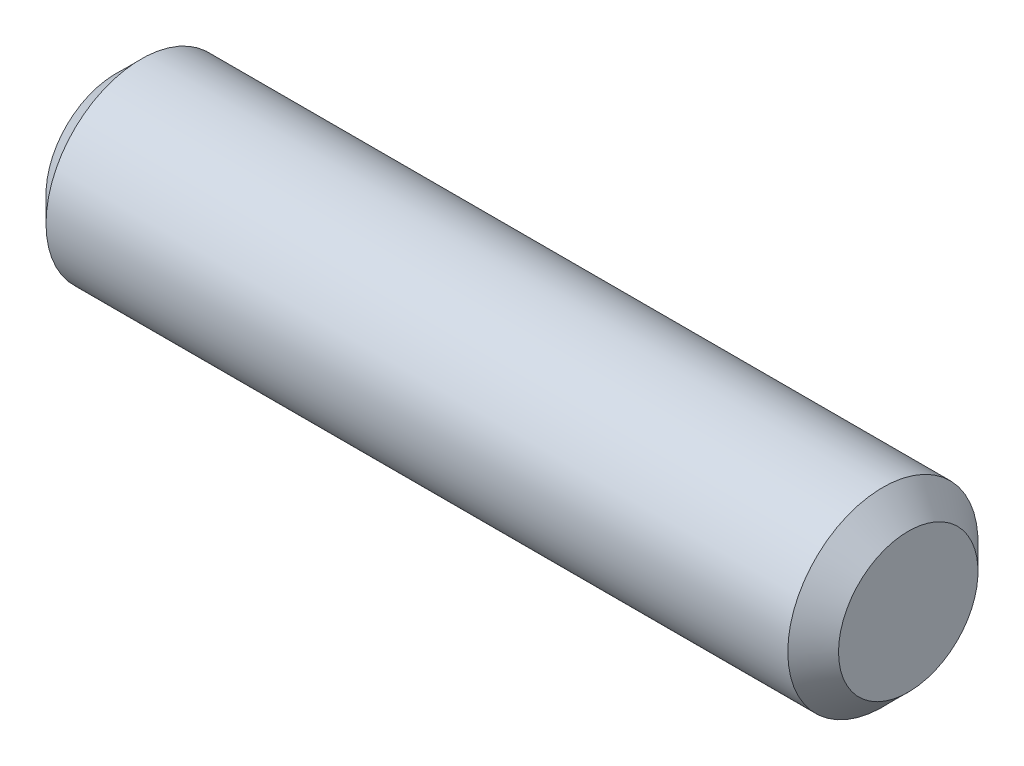
SolidWorks part; units mm, degrees
ref_plane "前视基准面" through (0, 0, 0) normal (0, 0, 1) x (1, 0, 0)
ref_plane "上视基准面" through (0, 0, 0) normal (0, 1, 0) x (1, 0, 0)
ref_plane "右视基准面" through (0, 0, 0) normal (1, 0, 0) x (0, 0, -1)
sketch "草图1" plane through (0, 0, 0) normal (0, 0, 1) x (1, 0, 0)
  line L0 (-6.3202, 0) -> (6.9944, 0) construction
  line L1 (-5.3427, 0) -> (-5.3427, 3)
  line L2 (-5.3427, 3) -> (19.6573, 3)
  line L3 (19.6573, 3) -> (19.6573, 0)
  line L4 (-5.3427, 0) -> (19.6573, 0)
  dimension "D1" = 25
  dimension "D2" = 3
revolve "旋转1" add sketch "草图1" angle 360 about L0
chamfer "倒角1" distance 0.8 angle 45 2 edges at (-5.3427, 0, 3) (19.6573, 0, 3)
